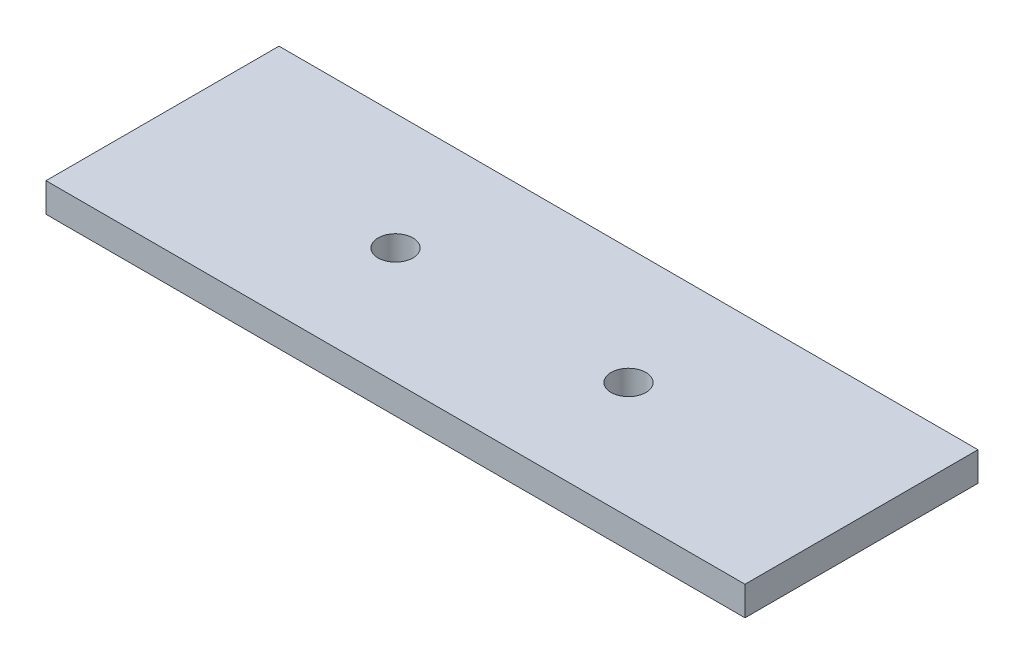
SolidWorks part; units mm, degrees
ref_plane "Front Plane" through (0, 0, 0) normal (0, 0, 1) x (1, 0, 0)
ref_plane "Top Plane" through (0, 0, 0) normal (0, 1, 0) x (1, 0, 0)
ref_plane "Right Plane" through (0, 0, 0) normal (1, 0, 0) x (0, 0, -1)
sketch "Sketch1" plane through (0, 0, 0) normal (0, 1, 0) x (1, 0, 0)
  line L1 (-38.1, -12.7) -> (38.1, -12.7)
  line L2 (-38.1, -12.7) -> (-38.1, 12.7)
  line L3 (-38.1, 12.7) -> (38.1, 12.7)
  line L4 (38.1, -12.7) -> (38.1, 12.7)
  line L5 (-38.1, -12.7) -> (38.1, 12.7) construction
  line L6 (-38.1, 12.7) -> (38.1, -12.7) construction
  point P0 (0, 0)
  dimension "D1" = 25.4
  dimension "D2" = 76.2
extrude "Boss-Extrude1" add sketch "Sketch1" along normal blind 3.175
hole_wizard "#6 Clearance Hole1" positions "Sketch2" profile "Sketch3" hole size "#6" standard "ANSI Inch" end condition through all
sketch "Sketch2" plane through (0, 3.175, 0) normal (0, 1, 0) x (1, 0, 0)
  line L0 (0, 0) -> (-12.7, 0) construction
  line L3 (0, 0) -> (12.7, 0) construction
  point P0 (-12.7, 0)
  point P2 (12.7, 0)
  dimension "D1" = 12.7
  dimension "D2" = 12.7
sketch "Sketch3" plane through (-12.7, 3.175, 0) normal (1, 0, 0) x (0, 0, 1)
  line L0 (0, 0) -> (0, 3.175)
  line L1 (0, 3.175) -> (1.8986, 3.175)
  line L2 (1.8986, 3.175) -> (1.8986, 0)
  line L5 (1.8986, 0) -> (0, 0)
  line L11 (0, -6.35) -> (0, 107.95) construction
  dimension "Thru Hole Dia." = 3.7973
  dimension "Thru Hole Depth" = 3.175
